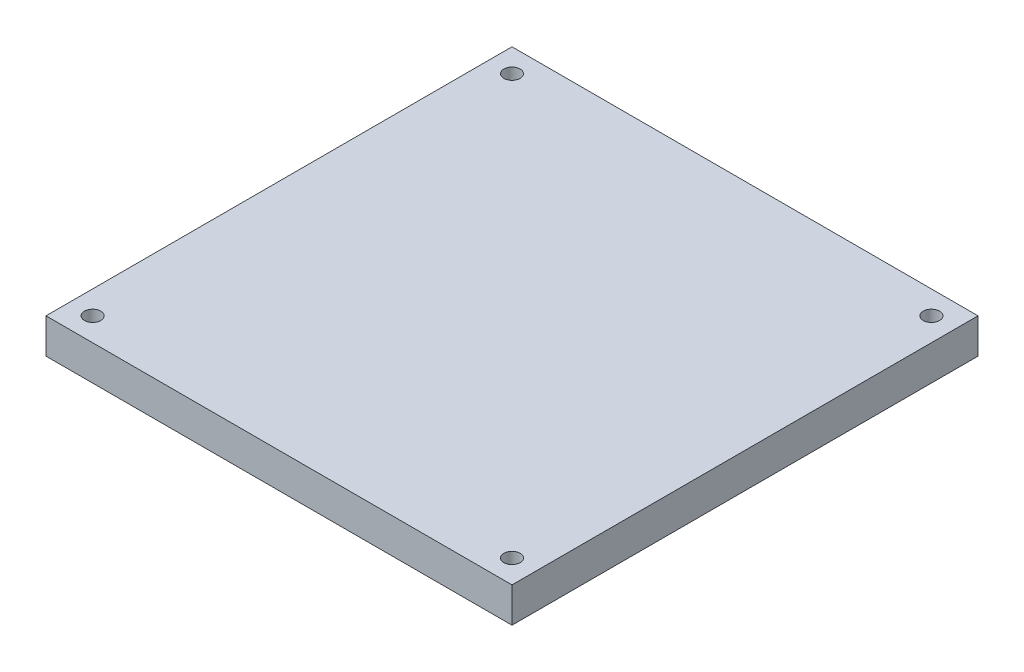
SolidWorks part; units mm, degrees
ref_plane "Front Plane" through (0, 0, 0) normal (0, 0, 1) x (1, 0, 0)
ref_plane "Top Plane" through (0, 0, 0) normal (0, 1, 0) x (1, 0, 0)
ref_plane "Right Plane" through (0, 0, 0) normal (1, 0, 0) x (0, 0, -1)
sketch "Sketch1" plane through (0, 0, 0) normal (0, 1, 0) x (1, 0, 0)
  line L1 (-100, -100) -> (100, -100)
  line L2 (-100, -100) -> (-100, 100)
  line L3 (-100, 100) -> (100, 100)
  line L4 (100, -100) -> (100, 100)
  line L5 (-100, -100) -> (100, 100) construction
  line L6 (-100, 100) -> (100, -100) construction
  point P0 (0, 0)
  dimension "D1" = 200
  dimension "D2" = 200
extrude "Boss-Extrude1" add sketch "Sketch1" along normal blind 15
hole_wizard "M8x1.0 Tapped Hole1" positions "Sketch3" profile "Sketch4" tap size "M8x1.0" standard "ANSI Metric" end condition through all
sketch "Sketch3" plane through (0, 0, 0) normal (0, -1, 0) x (-1, 0, 0)
  line L0 (100, -100) -> (-100, 100) construction
  line L2 (-100, -100) -> (100, 100) construction
  line L4 (100, 100) -> (100, -100) construction
  point P0 (90, 90)
  point P2 (90, -90)
  point P4 (-90, -90)
  point P6 (-90, 90)
  dimension "D1" = 10
sketch "Sketch4" plane through (-90, 0, -90) normal (1, 0, 0) x (0, 0, -1)
  line L0 (0, 0) -> (0, 15)
  line L1 (0, 15) -> (3.5, 15)
  line L2 (3.5, 15) -> (3.5, 0)
  line L5 (3.5, 0) -> (0, 0)
  line L11 (0, -6.35) -> (0, 107.95) construction
  dimension "Thru Tap Drill Dia." = 7
  dimension "Thru Tap Drill Depth" = 15
cosmetic thread "Hole Thread1" parameters "D2"=8
cosmetic thread "Hole Thread2" parameters "D2"=8
cosmetic thread "Hole Thread3" parameters "D2"=8
cosmetic thread "Hole Thread4" parameters "D2"=8
